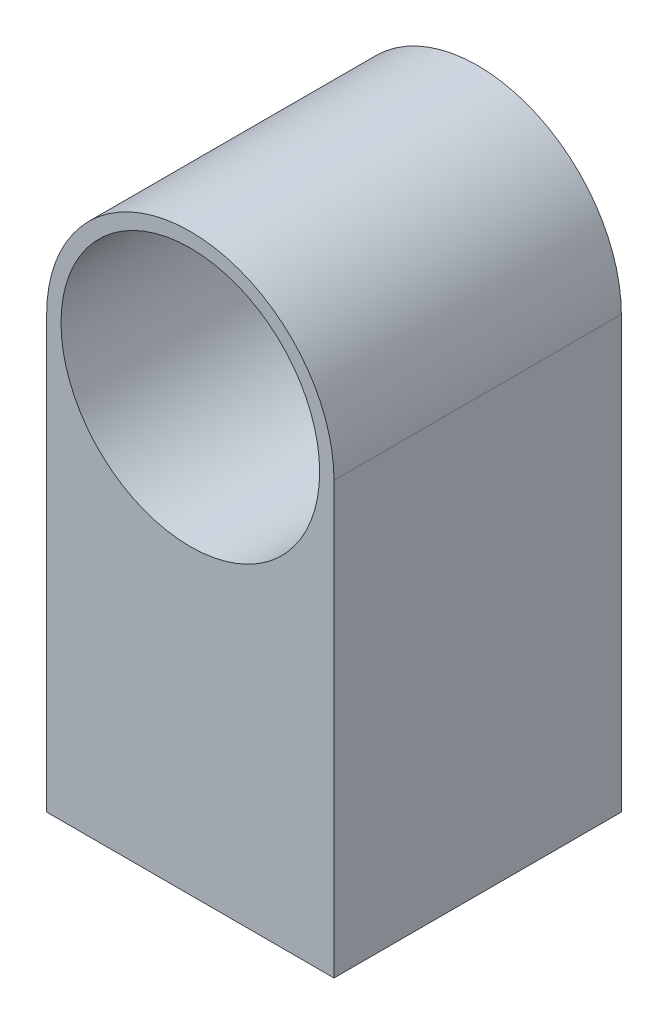
SolidWorks part; units mm, degrees
ref_plane "Front Plane" through (0, 0, 0) normal (0, 0, 1) x (1, 0, 0)
ref_plane "Top Plane" through (0, 0, 0) normal (0, 1, 0) x (1, 0, 0)
ref_plane "Right Plane" through (0, 0, 0) normal (1, 0, 0) x (0, 0, -1)
sketch "Sketch1" plane through (0, 0, 0) normal (0, 0, 1) x (1, 0, 0)
  line L2 (0, 0) -> (0, -150)
  line L3 (0, -150) -> (100, -150)
  line L4 (100, 0) -> (100, -150)
  arc A0 (0, 0) -> (100, 0) centre (50, 0) cw
  circle A1 centre (50, 0) radius 45
  dimension "D3" = 90
  dimension "D1" = 150
  dimension "D2" = 100
extrude "Boss-Extrude1" add sketch "Sketch1" along normal blind 100
